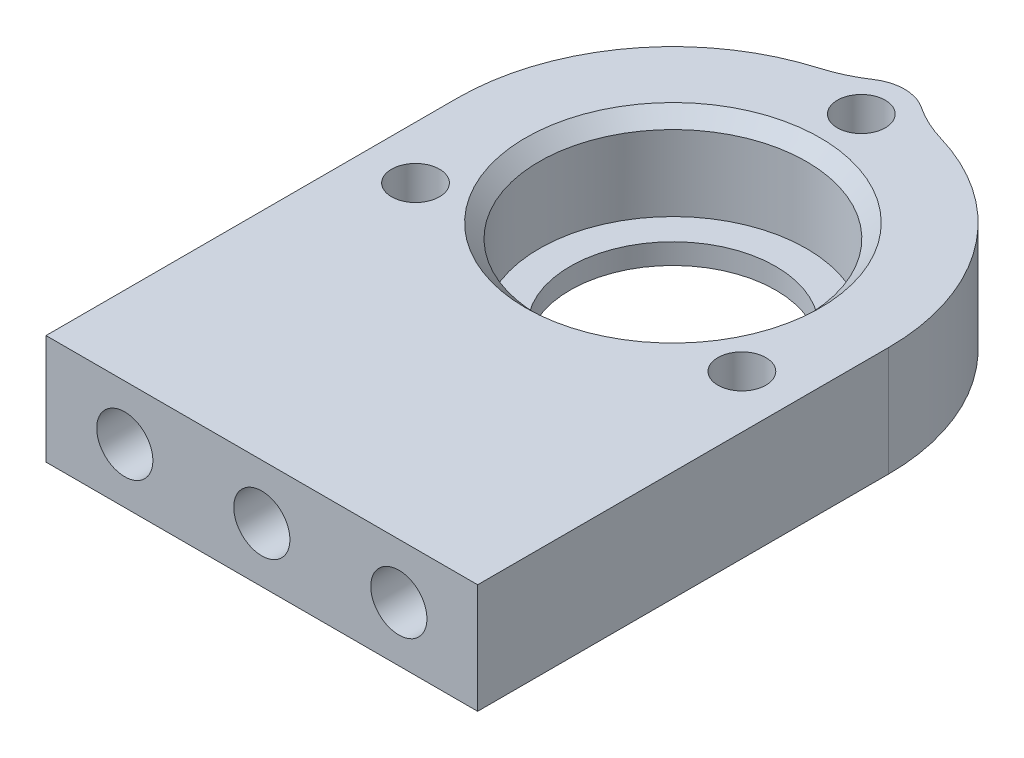
SolidWorks part; units mm, degrees
material "PETG"
ref_plane "Спереди" through (0, 0, 0) normal (0, 0, 1) x (1, 0, 0)
ref_plane "Сверху" through (0, 0, 0) normal (0, 1, 0) x (1, 0, 0)
ref_plane "Справа" through (0, 0, 0) normal (1, 0, 0) x (0, 0, -1)
sketch "Эскиз1" plane through (0, 0, 0) normal (0, 1, 0) x (1, 0, 0)
  line L0 (0, 0) -> (-22718.1109, 0) construction
  line L1 (0, 0) -> (0, 22718.1109) construction
  line L2 (-15.75, 0) -> (15.75, 0)
  line L3 (15.75, 0) -> (15.75, 30)
  line L4 (-15.75, 0) -> (-15.75, 30)
  arc A0 (15.75, 30) -> (-15.75, 30) centre (0, 30) ccw
  circle A1 centre (0, 30) radius 9.75
  point P12 (0, 0)
  dimension "D2" = 6
  dimension "D3" = 19.5
  dimension "D1" = 30
extrude "Бобышка-Вытянуть1" add sketch "Эскиз1" along normal blind 8
sketch "Эскиз2" plane through (0, 0, 0) normal (0, 0, 1) x (1, 0, 0)
  line L0 (-20, 4) -> (49980, 4) construction
  line L1 (-15.75, 8) -> (-15.75, 0) construction
  line L2 (15.75, 8) -> (15.75, 0) construction
  line L3 (0, 0) -> (0, 50000) construction
  circle A0 centre (0, 4) radius 2.05
  circle A1 centre (-10, 4) radius 2.05
  circle A2 centre (10, 4) radius 2.05
  point P4 (-15.75, 4)
  point P7 (15.75, 4)
  dimension "D1" = 4.1
  dimension "D2" = 20
extrude "Вырез-Вытянуть1" cut sketch "Эскиз2" against normal blind 6
sketch "Эскиз4" plane through (0, 0, 0) normal (0, -1, 0) x (1, 0, 0)
  circle A0 centre (0, -30) radius 9.75 construction
  circle A1 centre (0, -30) radius 9.75
  circle A2 centre (0, -30) radius 7.5
  dimension "D1" = 15
extrude "Бобышка-Вытянуть2" add sketch "Эскиз4" against normal blind 1.5
sketch "Эскиз5" plane through (0, 8, 0) normal (0, 1, 0) x (1, 0, 0)
  line L0 (0, 30) -> (0, 50030) construction
  line L1 (0, 30) -> (-50000, 30) construction
  circle A0 centre (0, 43.75) radius 1.75 construction
  arc A1 (2.5957, 45.5346) -> (-2.5957, 45.5346) centre (0, 43.75) ccw
  arc A2 (15.75, 30) -> (-15.75, 30) centre (0, 30) ccw construction
  arc A3 (2.5957, 45.5346) -> (-2.5957, 45.5346) centre (0, 30) ccw
  dimension "D2" = 3.5
  dimension "D3" = 6.3
  dimension "D1" = 13.75
extrude "Бобышка-Вытянуть3" add sketch "Эскиз5" against normal up to surface (8 mm away) up to face at (0, 0, -18.9375)
sketch "Эскиз6" plane through (0, 8, 0) normal (0, 1, 0) x (1, 0, 0)
  line L0 (0, 30) -> (0, -49970) construction
  line L1 (0, 30) -> (50000, 30) construction
  circle A0 centre (0, 43.75) radius 1.75
  arc A1 (2.5957, 45.5346) -> (-2.5957, 45.5346) centre (0, 43.75) ccw construction
  circle A2 centre (11.9078, 23.125) radius 1.75
  circle A3 centre (-11.9078, 23.125) radius 1.75
  point P10 (0, 30)
  point P17 (0, 30)
  dimension "D1" = 3.5
  dimension "D2" = 3
extrude "Вырез-Вытянуть2" cut sketch "Эскиз6" against normal blind 4
fillet "Скругление1" radius 10 2 edges at (-2.5957, 4, -45.5346) (2.5957, 4, -45.5346)
chamfer "Фаска1" distance 1 angle 45 1 edges at (0, 8, -20.25)
